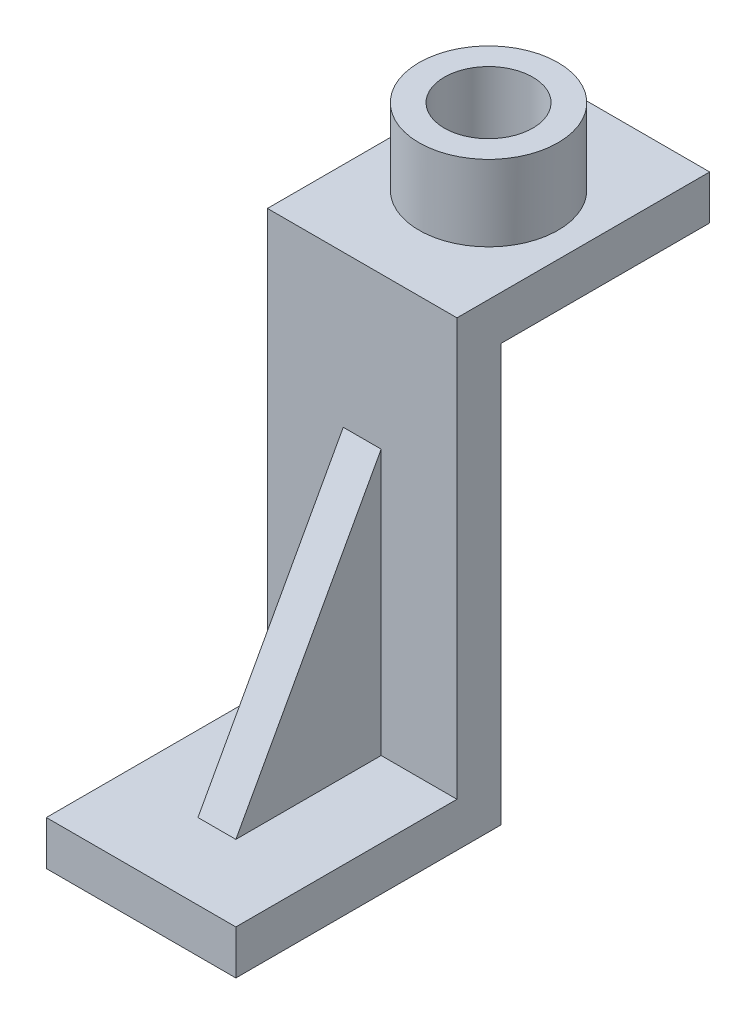
SolidWorks part; units mm, degrees
ref_plane "Front Plane" through (0, 0, 0) normal (0, 0, 1) x (1, 0, 0)
ref_plane "Top Plane" through (0, 0, 0) normal (0, 1, 0) x (1, 0, 0)
ref_plane "Right Plane" through (0, 0, 0) normal (1, 0, 0) x (0, 0, -1)
sketch "Sketch1" plane through (0, 0, 0) normal (0, 0, 1) x (1, 0, 0)
  line L1 (0, 0) -> (30, 0)
  line L2 (0, 0) -> (0, 66)
  line L3 (0, 66) -> (30, 66)
  line L4 (30, 0) -> (30, 66)
  dimension "D1" = 30
  dimension "D2" = 66
extrude "Boss-Extrude1" add sketch "Sketch1" along normal mid plane 42
sketch "Sketch2" plane through (0, 0, 21) normal (0, 0, 1) x (1, 0, 0)
  line L1 (0, 66) -> (0, 0) construction
  line L3 (30, 0) -> (30, 66) construction
  line L6 (0, 7) -> (0, 66)
  line L7 (0, 66) -> (30, 66)
  line L8 (30, 66) -> (30, 7)
  line L9 (0, 7) -> (30, 7)
  line L10 (0, 0) -> (30, 0) construction
  dimension "D1" = 7
extrude "Cut-Extrude1" cut sketch "Sketch2" against normal through all
sketch "Sketch4" plane through (0, 7, 0) normal (0, 1, 0) x (1, 0, 0)
  line L0 (0, 21) -> (30, 21)
  line L1 (30, 21) -> (30, 14)
  line L2 (30, 21) -> (30, -21) construction
  line L3 (30, 14) -> (0, 14)
  line L4 (0, 21) -> (0, -21) construction
  line L5 (0, 14) -> (0, 21)
  dimension "D1" = 7
extrude "Boss-Extrude2" add sketch "Sketch4" along normal blind 66
sketch "Sketch9" plane through (0, 0, -14) normal (0, 0, 1) x (1, 0, 0)
  line L0 (0, 73) -> (30, 73)
  line L1 (30, 73) -> (30, 66)
  line L2 (30, 73) -> (30, 7) construction
  line L3 (30, 66) -> (0, 66)
  line L4 (0, 73) -> (0, 7) construction
  line L5 (0, 66) -> (0, 73)
  dimension "D1" = 7
extrude "Boss-Extrude3" add sketch "Sketch9" against normal blind 40
sketch "Sketch10" plane through (0, 73, 0) normal (0, 1, 0) x (1, 0, 0)
  line L0 (0, 14) -> (30, 14) construction
  line L2 (30, 14) -> (30, 54) construction
  circle A0 centre (15, 34) radius 7
  circle A1 centre (15, 34) radius 11
  point P7 (0, 0)
  dimension "D1" = 22
  dimension "D2" = 14
  dimension "D3" = 20
  dimension "D4" = 15
extrude "Boss-Extrude4" add sketch "Sketch10" along normal blind 12
ref_plane "Plane1" through (15, 0, 0) normal (1, 0, 0) x (0, 0, -1)
sketch "Sketch18" plane through (15, 0, 0) normal (1, 0, 0) x (0, 0, -1)
  line L0 (14, 49) -> (-9, 7)
  line L1 (14, 73) -> (14, 7) construction
  line L2 (14, 7) -> (-21, 7) construction
  line L3 (-9, 7) -> (14, 7)
  line L4 (14, 7) -> (14, 49)
  dimension "D1" = 42
  dimension "D2" = 23
extrude "Boss-Extrude6" add sketch "Sketch18" along normal mid plane 6
